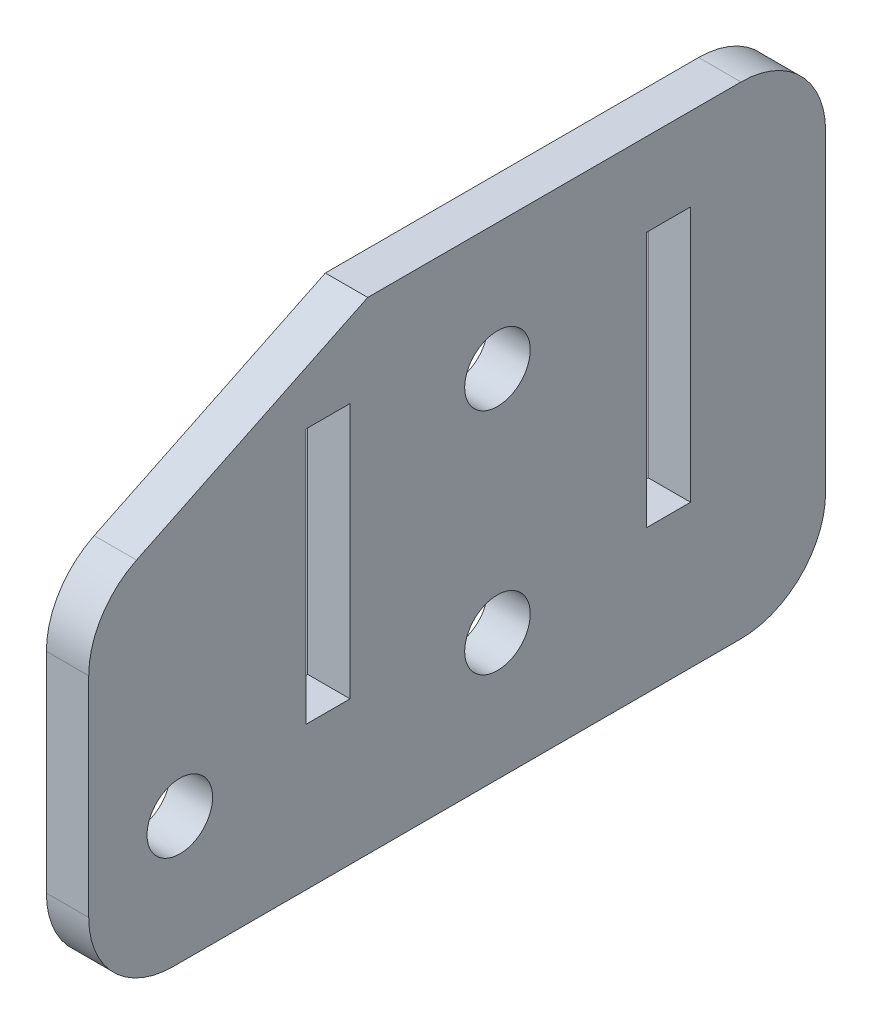
SolidWorks part; units mm, degrees
material "AISI 4340 Steel, annealed"
ref_plane "X-Y Datum" through (0, 0, 0) normal (0, 0, 1) x (1, 0, 0)
ref_plane "X-Z Datum" through (0, 0, 0) normal (0, 1, 0) x (1, 0, 0)
ref_plane "Y-Z Datum" through (0, 0, 0) normal (1, 0, 0) x (0, 0, -1)
sketch "Sketch1" plane through (0, 0, 0) normal (1, 0, 0) x (0, 0, -1)
  line L13 (55.245, 0) -> (55.245, 36.1544)
  line L14 (55.245, 36.1544) -> (20.9147, 36.1544)
  line L15 (20.9147, 36.1544) -> (0, 26.034)
  line L16 (0, 26.034) -> (0, 0)
  line L17 (0, 0) -> (55.245, 0)
  point P6 (0, 13.017)
  dimension "D1" = 55.245
  dimension "D2" = 36.1544
  dimension "D3" = 20.9147
  dimension "D4" = 26.034
extrude "Boss-Extrude1" add sketch "Sketch1" along normal blind 3.175
sketch "Sketch7" plane through (0, 0, 0) normal (-1, 0, 0) x (0, 0, 1)
  line L8 (-55.245, 0) -> (-55.245, 36.1544) construction
  line L9 (-45.1202, 10.7544) -> (-41.8182, 10.7544)
  line L10 (-45.1202, 10.7544) -> (-45.1202, 29.9314)
  line L11 (-45.1202, 29.9314) -> (-41.8182, 29.9314)
  line L20 (-41.8182, 10.7544) -> (-41.8182, 29.9314)
  line L21 (-19.5932, 10.7544) -> (-16.2912, 10.7544)
  line L22 (-19.5932, 10.7544) -> (-19.5932, 29.9314)
  line L23 (-19.5932, 29.9314) -> (-16.2912, 29.9314)
  line L24 (-16.2912, 10.7544) -> (-16.2912, 29.9314)
  line L26 (-55.245, 36.1544) -> (-20.9147, 36.1544) construction
  dimension "D1" = 19.177
  dimension "D2" = 3.302
  dimension "D3" = 10.1248
  dimension "D4" = 6.223
  dimension "D5" = 22.225
extrude "Cut-Extrude1" cut sketch "Sketch7" against normal blind 3.175
sketch "Sketch8" plane through (0, 0, 0) normal (-1, 0, 0) x (0, 0, 1)
  line L0 (0, 0) -> (-55.245, 0) construction
  line L1 (-41.8182, 10.7544) -> (-41.8182, 29.9314) construction
  point P0 (-30.6422, 9.525)
  point P1 (-30.6422, 26.67)
  point P2 (-6.8297, 9.525)
  dimension "D1" = 17.145
  dimension "D2" = 9.525
  dimension "D3" = 23.8125
  dimension "D4" = 11.176
fillet "Fillet1" radius 6.35 4 edges at (1.5875, 26.034, 0) (1.5875, 0, 0) (1.5875, 36.1544, -55.245) (1.5875, 0, -55.245)
hole_wizard "#10 (0.1935) Diameter Hole2" positions "Sketch9" profile "Sketch10" hole size "#10" standard "ANSI Inch"
sketch "Sketch9" plane through (0, 0, 0) normal (-1, 0, 0) x (0, 0, 1)
  point P0 (-30.6422, 9.525)
  point P3 (-30.6422, 26.67)
  point P6 (-6.8297, 9.525)
sketch "Sketch10" plane through (0, 9.525, -30.6422) normal (0, 1, 0) x (0, 0, 1)
  line L0 (0, 0) -> (0, 11.176)
  line L1 (0, 11.176) -> (2.4574, 9.6994)
  line L2 (2.4574, 9.6994) -> (2.4574, 0)
  line L5 (2.4574, 0) -> (0, 0)
  line L10 (0, 11.176) -> (-2.4575, 9.6994) construction
  line L11 (0, -6.35) -> (0, 107.95) construction
  dimension "Hole Dia." = 4.9149
  dimension "Hole Depth" = 11.176
  dimension "Drill Angle" = 118
